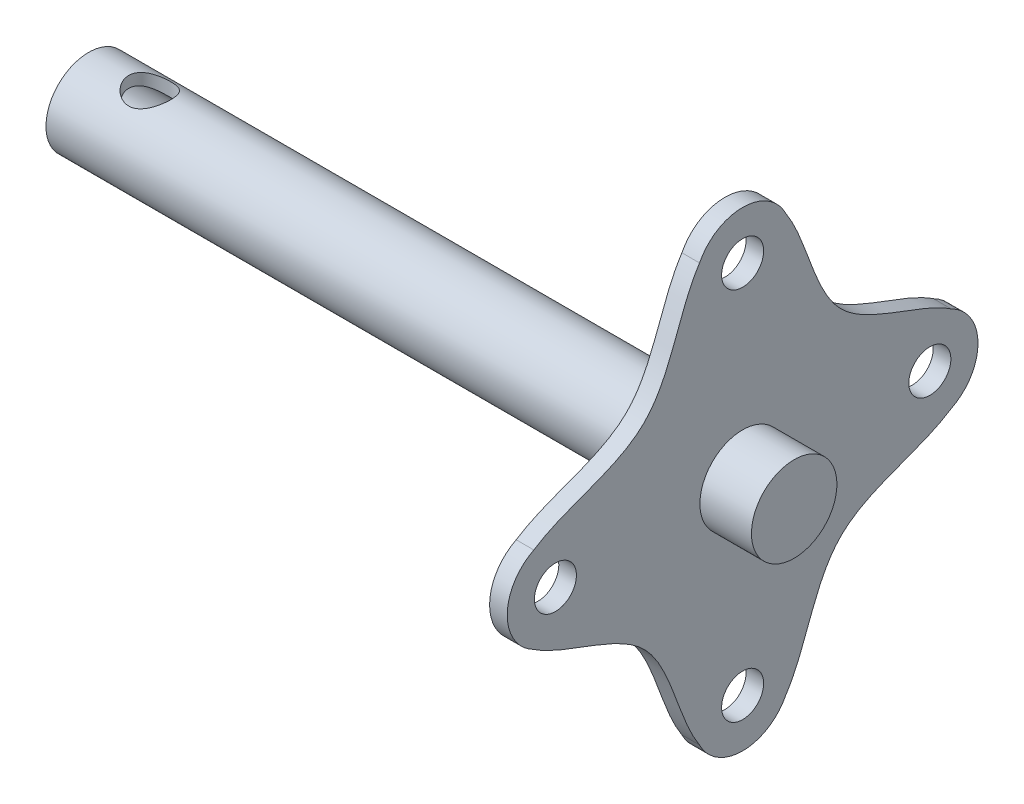
SolidWorks part; units mm, degrees
ref_plane "Front Plane" through (0, 0, 0) normal (0, 0, 1) x (1, 0, 0)
ref_plane "Top Plane" through (0, 0, 0) normal (0, 1, 0) x (1, 0, 0)
ref_plane "Right Plane" through (0, 0, 0) normal (1, 0, 0) x (0, 0, -1)
sketch "Sketch2" plane through (0, 0, 0) normal (0, 0, 1) x (1, 0, 0)
  line L0 (-78.74, 8.001) -> (-78.74, 5.9018)
  line L1 (-78.74, 8.001) -> (40.386, 8.001)
  line L2 (40.386, 8.001) -> (40.386, 44.069)
  line L3 (40.386, 44.069) -> (43.688, 44.069)
  line L4 (43.688, 44.069) -> (43.688, 8.001)
  line L5 (43.688, 8.001) -> (53.34, 8.001)
  line L6 (53.34, 8.001) -> (53.34, 0)
  line L7 (-53.34, 0) -> (53.34, 0)
  line L8 (-78.74, 5.9018) -> (-53.34, 5.9018)
  line L9 (-53.34, 5.9018) -> (-53.34, 0)
  point P0 (0, 0)
revolve "Revolve1" add sketch "Sketch2" angle 360 about L7
hole_wizard "Hole1" positions "3DSketch2" profile "Sketch4" legacy
sketch3d "3DSketch2"
  point P0 (-67.31, 8.001, 0)
sketch "Sketch4" plane through (-67.31, 8.001, 0) normal (1, 0, 0) x (0, 0, 1)
  line L0 (0, 0) -> (0, 7.62)
  line L1 (0, 7.62) -> (3.937, 7.62)
  line L2 (3.937, 7.62) -> (3.937, 0)
  line L5 (3.937, 0) -> (0, 0)
  line L10 (0, 7.62) -> (-3.937, 7.62) construction
  line L11 (0, -6.35) -> (0, 107.95) construction
  dimension "Hole Dia." = 7.874
  dimension "Hole Depth" = 7.62
  dimension "Drill Angle" = 180
sketch "Sketch5" plane through (0, 0, 0) normal (1, 0, 0) x (0, 0, -1)
  circle A0 centre (0, 0) radius 35.052 construction
  circle A1 centre (0, 0) radius 44.069
  arc A2 (-44.069, 0) -> (-39.0864, 8.0641) centre (-35.052, 0) cw
  arc A4 (0, 44.069) -> (8.0641, 39.0864) centre (0, 35.052) cw
  arc A5 (0, 44.069) -> (-8.0641, 39.0864) centre (0, 35.052) ccw
  circle A6 centre (0, 0) radius 44.069 construction
  circle A7 centre (0, 35.052) radius 3.937
  arc A10 (44.069, 0) -> (39.0864, 8.0641) centre (35.052, 0) ccw
  arc A11 (44.069, 0) -> (39.0864, -8.0641) centre (35.052, 0) cw
  circle A12 centre (35.052, 0) radius 3.937
  arc A14 (0, -44.069) -> (8.0641, -39.0864) centre (0, -35.052) ccw
  arc A15 (0, -44.069) -> (-8.0641, -39.0864) centre (0, -35.052) cw
  circle A16 centre (0, -35.052) radius 3.937
  circle A17 centre (-35.052, 0) radius 3.937
  arc A18 (-44.069, 0) -> (-39.0864, -8.0641) centre (-35.052, 0) ccw
  spline S0 degree 3 poles (-39.0864, 8.0641) (-32.8637, 12.1825) (-14.2948, 14.2958) (-12.1823, 32.8644) (-8.0641, 39.0864) knots 0 0 0 0 0.500028 1 1 1 1
  spline S1 degree 3 poles (8.0641, 39.0864) (12.1825, 32.8633) (14.2969, 14.295) (32.8647, 12.182) (39.0864, 8.0641) knots 0 0 0 0 0.500051 1 1 1 1
  spline S2 degree 3 poles (39.0864, -8.0641) (32.8633, -12.1825) (14.295, -14.2969) (12.182, -32.8647) (8.0641, -39.0864) knots 0 0 0 0 0.500051 1 1 1 1
  spline S3 degree 3 poles (-8.0641, -39.0864) (-12.1825, -32.8633) (-14.2969, -14.295) (-32.8647, -12.182) (-39.0864, -8.0641) knots 0 0 0 0 0.500051 1 1 1 1
  point P4 (-18.4083, 18.4102)
  point P12 (-10.9621, 33.2938)
  point P13 (-33.2938, 10.9621)
  point P14 (0, 0)
  point P22 (-8.0641, 39.0864)
  point P35 (10.9621, 33.2938)
  point P37 (39.0864, 8.0641)
  point P48 (33.2938, -10.9621)
  point P50 (8.0641, -39.0864)
  point P61 (-10.9621, -33.2938)
  point P63 (-39.0864, -8.0641)
  point P67 (0, 0)
  dimension "D1" = 4
extrude "Cut-Extrude5" cut sketch "Sketch5" along normal up to surface (43.688 mm away) contours A2 S0 A5 A1 | A15 S3 A18 A1 | A16 | A11 S2 A14 A1 | A12 | A4 S1 A10 A1 | A7 | A17 up to face at (43.688, -44.069, 0)
